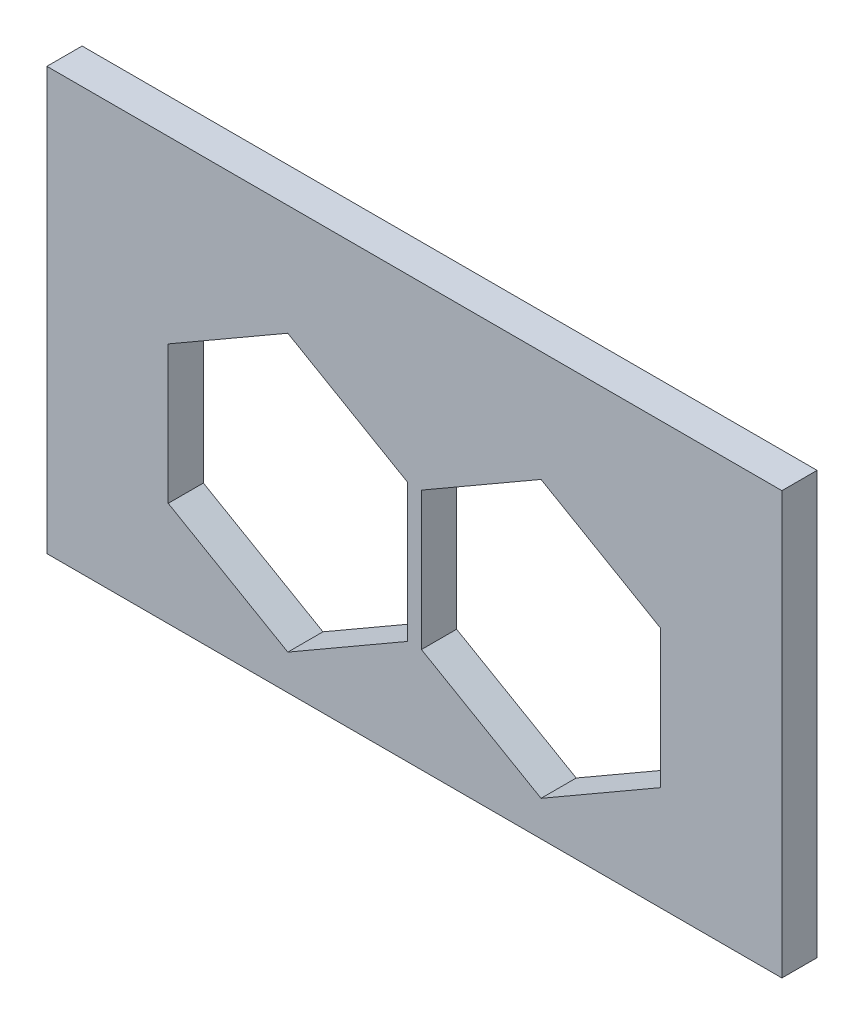
SolidWorks part; units mm, degrees
ref_plane "Front Plane" through (0, 0, 0) normal (0, 0, 1) x (1, 0, 0)
ref_plane "Top Plane" through (0, 0, 0) normal (0, 1, 0) x (1, 0, 0)
ref_plane "Right Plane" through (0, 0, 0) normal (1, 0, 0) x (0, 0, -1)
sketch "Sketch1" plane through (0, 0, 0) normal (0, 0, 1) x (1, 0, 0)
  line L1 (33.1749, -19.05) -> (-33.1749, -19.05)
  line L2 (33.1749, -19.05) -> (33.1749, 19.05)
  line L3 (33.1749, 19.05) -> (-33.1749, 19.05)
  line L4 (-33.1749, -19.05) -> (-33.1749, 19.05)
  line L5 (33.1749, -19.05) -> (-33.1749, 19.05) construction
  line L6 (33.1749, 19.05) -> (-33.1749, -19.05) construction
  line L39 (0, -19.05) -> (0, 19.05) construction
  line L40 (11.43, -3.41) -> (0, -3.41) construction
  line L41 (11.43, -15.875) -> (22.225, -9.6425)
  line L42 (22.225, -9.6425) -> (22.225, 2.8225)
  line L43 (22.225, 2.8225) -> (11.43, 9.055)
  line L44 (11.43, 9.055) -> (0.635, 2.8225)
  line L45 (0.635, 2.8225) -> (0.635, -9.6425)
  line L46 (0.635, -9.6425) -> (11.43, -15.875)
  line L47 (-0.635, -9.6425) -> (-11.43, -15.875)
  line L48 (-0.635, 2.8225) -> (-0.635, -9.6425)
  line L49 (-11.43, 9.055) -> (-0.635, 2.8225)
  line L50 (-22.225, 2.8225) -> (-11.43, 9.055)
  line L51 (-22.225, -9.6425) -> (-22.225, 2.8225)
  line L52 (-11.43, -15.875) -> (-22.225, -9.6425)
  circle A12 centre (11.43, -3.41) radius 10.795 construction
  point P0 (0, 0)
  dimension "D1" = 66.3499
  dimension "D2" = 38.1
  dimension "D14" = 11.43
  dimension "D15" = 24.93
  dimension "D16" = 3.175
extrude "Boss-Extrude1" add sketch "Sketch1" along normal blind 3.175
